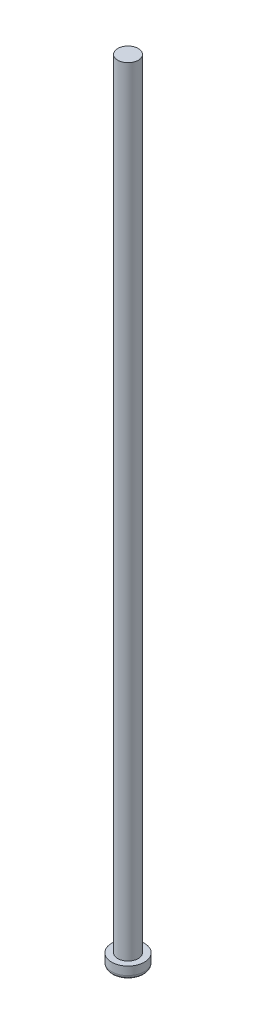
SolidWorks part; units mm, degrees
ref_plane "前视" through (0, 0, 0) normal (0, 0, 1) x (1, 0, 0)
ref_plane "上视" through (0, 0, 0) normal (0, 1, 0) x (1, 0, 0)
ref_plane "右视" through (0, 0, 0) normal (1, 0, 0) x (0, 0, -1)
sketch "草图1" plane through (0, 0, 0) normal (0, 1, 0) x (1, 0, 0)
  circle A0 centre (0, 0) radius 2.5
  dimension "D1" = 5
extrude "凸台-拉伸1" add sketch "草图1" along normal blind 190
cosmetic thread "装饰螺纹线1" parameters "D1"=5, "D2"=4.9
sketch "草图2" plane through (0, 0, 0) normal (0, -1, 0) x (1, 0, 0)
  circle A0 centre (0, 0) radius 4
  dimension "D1" = 8
extrude "凸台-拉伸2" add sketch "草图2" along normal blind 3
fillet "圆角1" radius 1 1 edges at (0, -3, -4)
